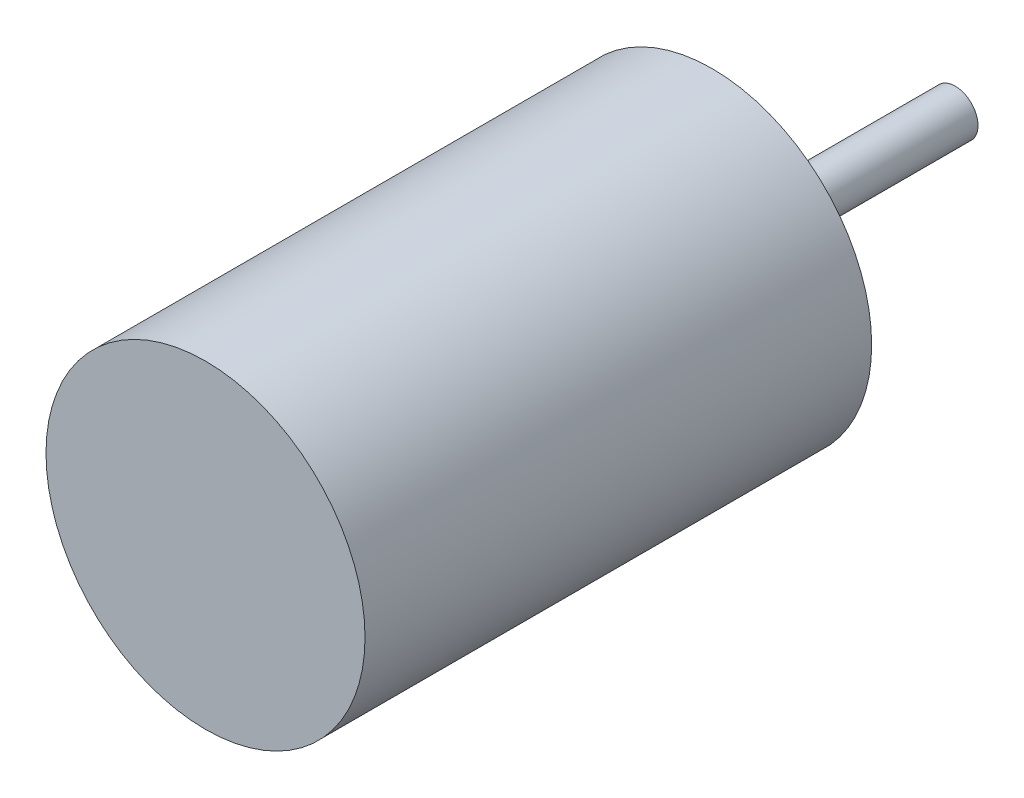
SolidWorks part; units mm, degrees
ref_plane "Front Plane" through (0, 0, 0) normal (0, 0, 1) x (1, 0, 0)
ref_plane "Top Plane" through (0, 0, 0) normal (0, 1, 0) x (1, 0, 0)
ref_plane "Right Plane" through (0, 0, 0) normal (1, 0, 0) x (0, 0, -1)
sketch "Sketch1" plane through (0, 0, 0) normal (0, 0, 1) x (1, 0, 0)
  circle A0 centre (0, 0) radius 3
extrude "Boss-Extrude1" add sketch "Sketch1" along normal blind 32
sketch "Sketch2" plane through (0, 0, 32) normal (0, 0, 1) x (1, 0, 0)
  circle A0 centre (0, 0) radius 21
extrude "Boss-Extrude2" add sketch "Sketch2" along normal blind 66.7
